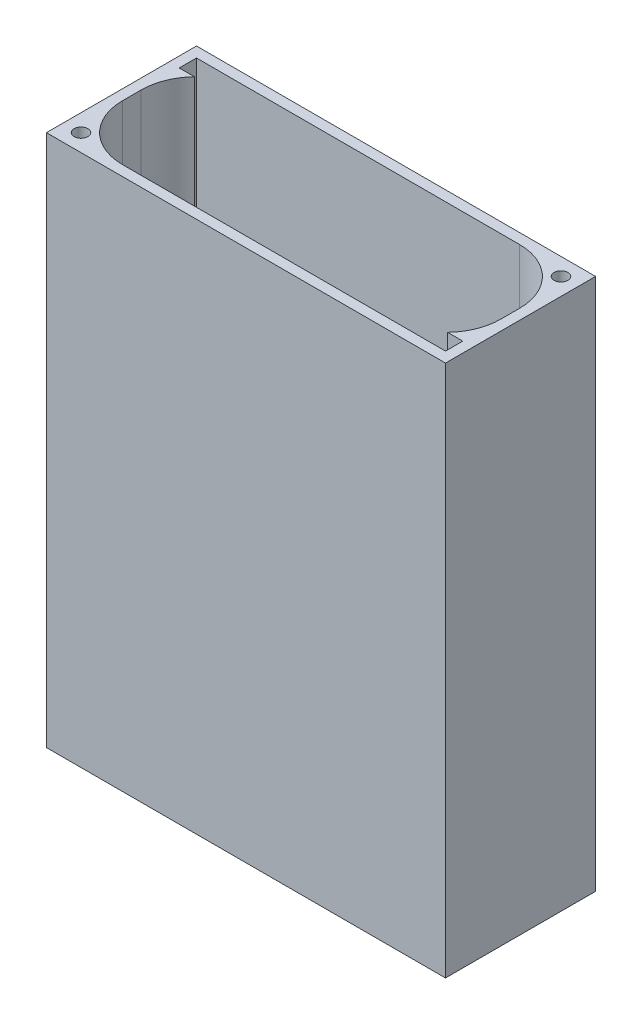
SolidWorks part; units mm, degrees
ref_plane "Front" through (0, 0, 0) normal (0, 0, 1) x (1, 0, 0)
ref_plane "Top" through (0, 0, 0) normal (0, 1, 0) x (1, 0, 0)
ref_plane "Right" through (0, 0, 0) normal (1, 0, 0) x (0, 0, -1)
sketch "Sketch1" plane through (0, 0, 0) normal (0, 1, 0) x (1, 0, 0)
  line L1 (0, 0) -> (57.7, 0)
  line L2 (0, 0) -> (0, 21.7)
  line L3 (0, 21.7) -> (57.7, 21.7)
  line L4 (57.7, 0) -> (57.7, 21.7)
  dimension "D1" = 21.7
  dimension "D2" = 57.7
extrude "Boss-Extrude1" add sketch "Sketch1" along normal blind 2
sketch "Sketch2" plane through (0, 2, 0) normal (0, 1, 0) x (1, 0, 0)
  line L0 (1.5, 20.2) -> (1.5, 1.5)
  line L1 (0, 21.7) -> (57.7, 21.7)
  line L2 (0, 21.7) -> (0, 0)
  line L3 (0, 0) -> (57.7, 0)
  line L4 (57.7, 21.7) -> (57.7, 0)
  line L5 (1.5, 1.5) -> (56.2, 1.5)
  line L6 (56.2, 20.2) -> (56.2, 1.5)
  line L7 (1.5, 20.2) -> (56.2, 20.2)
  dimension "D1" = 1.5
extrude "Boss-Extrude2" add sketch "Sketch2" along normal blind 75
fillet "Fillet1" radius 8 4 edges at (56.2, 39.5, -1.5) (56.2, 39.5, -20.2) (1.5, 39.5, -1.5) (1.5, 39.5, -20.2)
sketch "Sketch3" plane through (0, 77, 0) normal (0, 1, 0) x (1, 0, 0)
  line L0 (1.5, 12.2) -> (1.5, 9.5) construction
  line L1 (40.0836, 20.2) -> (1.5, 20.2)
  line L2 (40.0836, 20.2) -> (40.0836, 17.7)
  line L3 (40.0836, 17.7) -> (1.5, 17.7)
  line L4 (1.5, 20.2) -> (1.5, 17.7)
  line L6 (48.2, 20.2) -> (9.5, 20.2) construction
  dimension "D1" = 2.5
extrude "Cut-Extrude1" cut sketch "Sketch3" against normal up to surface (75 mm away) up to face at (28.85, 2, -10.85)
sketch "Sketch4" plane through (0, 77, 0) normal (0, 1, 0) x (1, 0, 0)
  line L0 (9.5, 1.5) -> (48.2, 1.5) construction
  line L1 (39.1106, 1.5) -> (56.2, 1.5)
  line L2 (39.1106, 1.5) -> (39.1106, 4)
  line L3 (39.1106, 4) -> (56.2, 4)
  line L4 (56.2, 1.5) -> (56.2, 4)
  dimension "D1" = 2.5
extrude "Cut-Extrude2" cut sketch "Sketch4" against normal blind 75
sketch "Sketch5" plane through (0, 77, 0) normal (0, 1, 0) x (1, 0, 0)
  line L0 (57.7, 21.7) -> (0, 21.7) construction
  line L1 (57.7, 0) -> (57.7, 21.7) construction
  line L2 (0, 21.7) -> (0, 0) construction
  line L3 (0, 0) -> (57.7, 0) construction
  circle A0 centre (55.2, 19.2) radius 1
  circle A1 centre (2.5, 2.5) radius 1
  dimension "D1" = 2
  dimension "D2" = 2
  dimension "D3" = 2.5
  dimension "D4" = 2.5
  dimension "D5" = 2.5
  dimension "D6" = 2.5
extrude "Cut-Extrude3" cut sketch "Sketch5" against normal blind 8
sketch "Sketch6" plane through (0, 2, 0) normal (0, 1, 0) x (1, 0, 0)
  line L0 (57.7, 21.7) -> (0, 21.7) construction
  line L1 (0, 21.7) -> (0, 0) construction
  circle A0 centre (28.85, 10.85) radius 1.5
  circle A1 centre (10.85, 10.85) radius 1.5
  circle A2 centre (46.85, 10.85) radius 1.5
  point P5 (28.85, 21.7)
  point P9 (0, 10.85)
  point P10 (0, 0)
  point P13 (0, 0)
  dimension "D1" = 3
  dimension "D4" = 3
  dimension "D5" = 3
  dimension "D2" = 18
  dimension "D3" = 18
extrude "Cut-Extrude4" cut sketch "Sketch6" against normal blind 10
